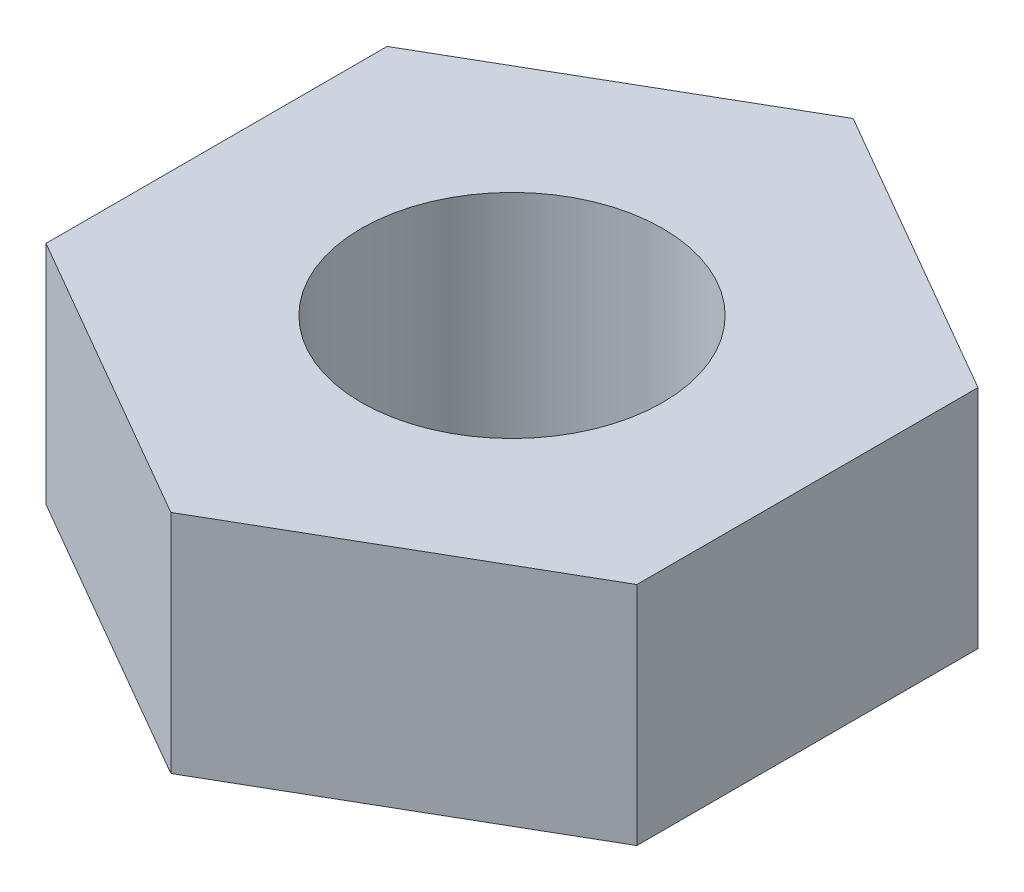
SolidWorks part; units mm, degrees
ref_plane "Front Plane" through (0, 0, 0) normal (0, 0, 1) x (1, 0, 0)
ref_plane "Top Plane" through (0, 0, 0) normal (0, 1, 0) x (1, 0, 0)
ref_plane "Right Plane" through (0, 0, 0) normal (1, 0, 0) x (0, 0, -1)
sketch "Sketch1" plane through (0, 0, 0) normal (0, 1, 0) x (1, 0, 0)
  line L1 (0, -2.2632) -> (1.96, -1.1316)
  line L2 (1.96, -1.1316) -> (1.96, 1.1316)
  line L3 (1.96, 1.1316) -> (0, 2.2632)
  line L4 (0, 2.2632) -> (-1.96, 1.1316)
  line L5 (-1.96, 1.1316) -> (-1.96, -1.1316)
  line L6 (-1.96, -1.1316) -> (0, -2.2632)
  circle A0 centre (0, 0) radius 1.96 construction
  circle A1 centre (0, 0) radius 1
  dimension "D2" = 2
  dimension "D1" = 3.92
extrude "Boss-Extrude1" add sketch "Sketch1" along normal blind 1.5
